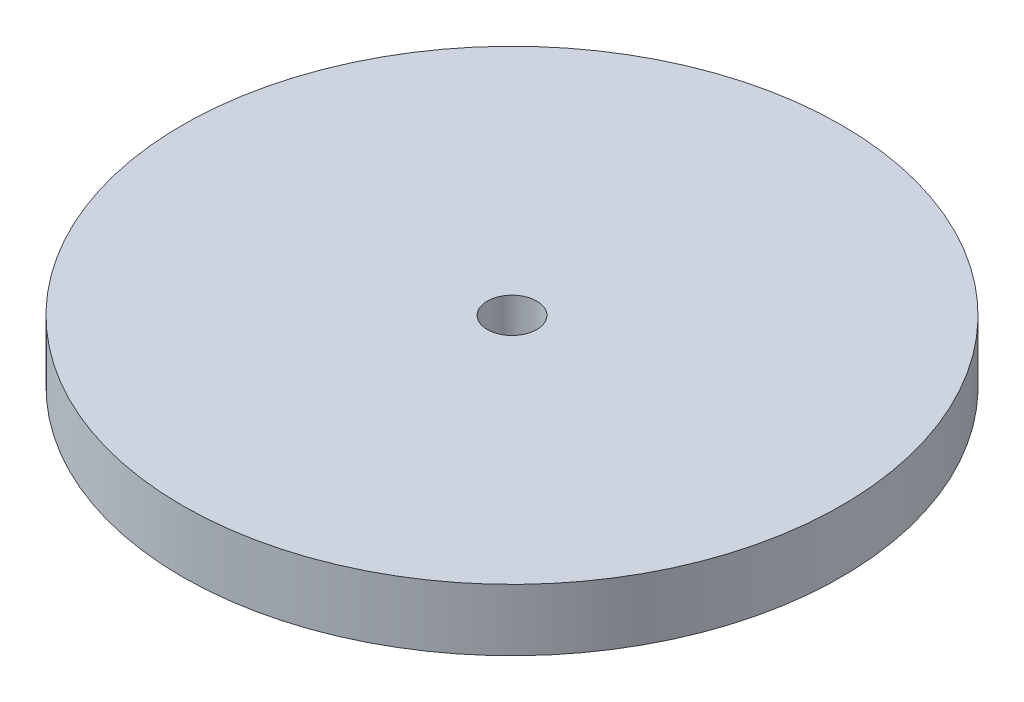
SolidWorks part; units mm, degrees
ref_plane "Plano frontal" through (0, 0, 0) normal (0, 0, 1) x (1, 0, 0)
ref_plane "Plano superior" through (0, 0, 0) normal (0, 1, 0) x (1, 0, 0)
ref_plane "Plano direito" through (0, 0, 0) normal (1, 0, 0) x (0, 0, -1)
sketch "Esboço1" plane through (0, 0, 0) normal (0, 1, 0) x (1, 0, 0)
  circle A0 centre (0, 0) radius 80
extrude "Ressalto-extrusão1" add sketch "Esboço1" along normal blind 15
sketch "Esboço2" plane through (0, 0, 0) normal (0, 1, 0) x (1, 0, 0)
  circle A0 centre (0, 0) radius 6
extrude "Corte-extrusão1" cut sketch "Esboço2" along normal blind 15
